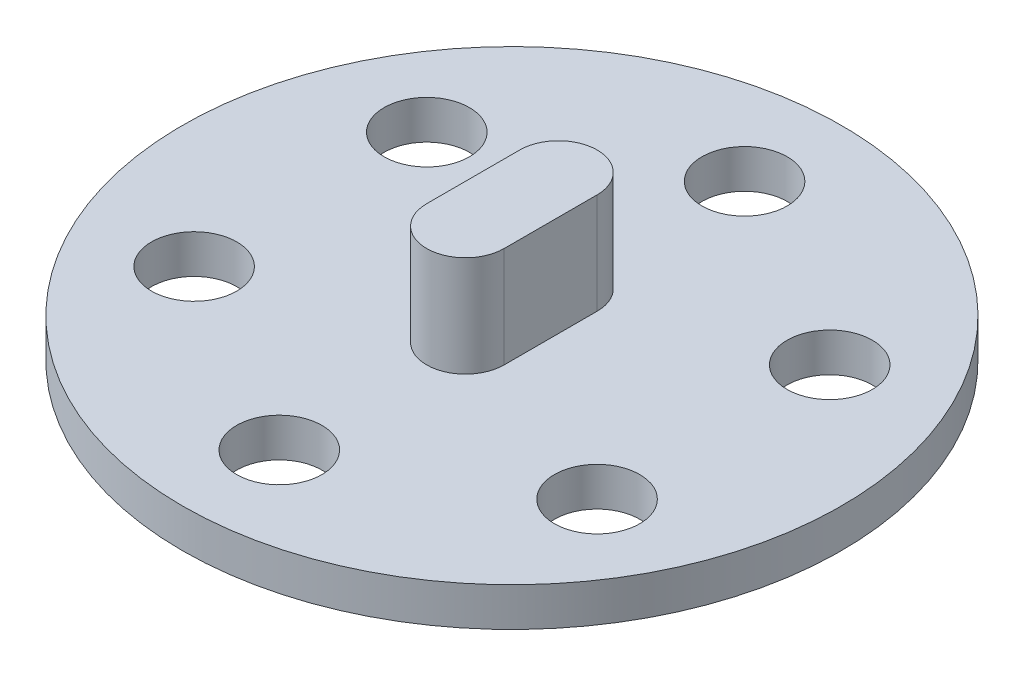
SolidWorks part; units mm, degrees
ref_plane "Front Plane" through (0, 0, 0) normal (0, 0, 1) x (1, 0, 0)
ref_plane "Top Plane" through (0, 0, 0) normal (0, 1, 0) x (1, 0, 0)
ref_plane "Right Plane" through (0, 0, 0) normal (1, 0, 0) x (0, 0, -1)
sketch "Sketch1" plane through (0, 0, 0) normal (0, 1, 0) x (1, 0, 0)
  line L0 (0, 0) -> (6, 0) construction
  line L1 (0, 0) -> (-6, 0) construction
  line L2 (-6, 0) -> (-6, 30) construction
  line L3 (6, 0) -> (6, 30) construction
  line L4 (-31.4808, 15) -> (-20.4808, 15) construction
  circle A31 centre (6, 0) radius 12 construction
  circle A32 centre (-6, 0) radius 12 construction
  circle A33 centre (-6, 30) radius 11 construction
  circle A34 centre (6, 30) radius 11 construction
  circle A35 centre (32.2308, 14.567) radius 11 construction
  circle A36 centre (31.9808, -15.866) radius 11 construction
  circle A37 centre (5.5, -30.866) radius 11 construction
  circle A38 centre (-20.7308, -15.433) radius 11 construction
  circle A39 centre (-20.4808, 15) radius 11 construction
  circle A40 centre (19.7308, 15.433) radius 11 construction
  circle A41 centre (19.9808, -14.134) radius 11 construction
  circle A42 centre (-5.5, -29.134) radius 11 construction
  circle A43 centre (-31.2308, -14.567) radius 11 construction
  circle A44 centre (-31.4808, 15) radius 11 construction
  circle A45 centre (0, 0) radius 30 construction
  circle A46 centre (-25.9808, 15) radius 5.5
  circle A47 centre (0, 30) radius 5.5
  circle A48 centre (25.9808, 15) radius 5.5
  circle A49 centre (25.9808, -15) radius 5.5
  circle A50 centre (0, -30) radius 5.5
  circle A51 centre (-25.9808, -15) radius 5.5
  circle A52 centre (0, 0) radius 42.5
  point P22 (5.75, -0.433)
  point P32 (-5.75, 0.433)
  point P33 (-25.9808, 15)
  point P50 (0, 0)
  dimension "D1" = 6
  dimension "D2" = 24
  dimension "D4" = 24
  dimension "D5" = 30
  dimension "D6" = 30
  dimension "D8" = 22
  dimension "D10" = 11
  dimension "D7" = 22
  dimension "D9" = 6
  dimension "D11" = 85
  dimension "D3" = 6
extrude "Boss-Extrude2" add sketch "Sketch1" along normal blind 5
sketch "Sketch2" plane through (0, 5, 0) normal (0, 1, 0) x (1, 0, 0)
  line L0 (0, -6) -> (0, 6) construction
  line L1 (-5, -6) -> (-5, 6)
  line L2 (5, -6) -> (5, 6)
  line L3 (-5, 0) -> (5, 0) construction
  arc A1 (-5, -6) -> (5, -6) centre (0, -6) ccw
  arc A2 (5, 6) -> (-5, 6) centre (0, 6) ccw
  point P5 (0, 0)
  dimension "D2" = 10
extrude "Boss-Extrude3" add sketch "Sketch2" along normal blind 13
